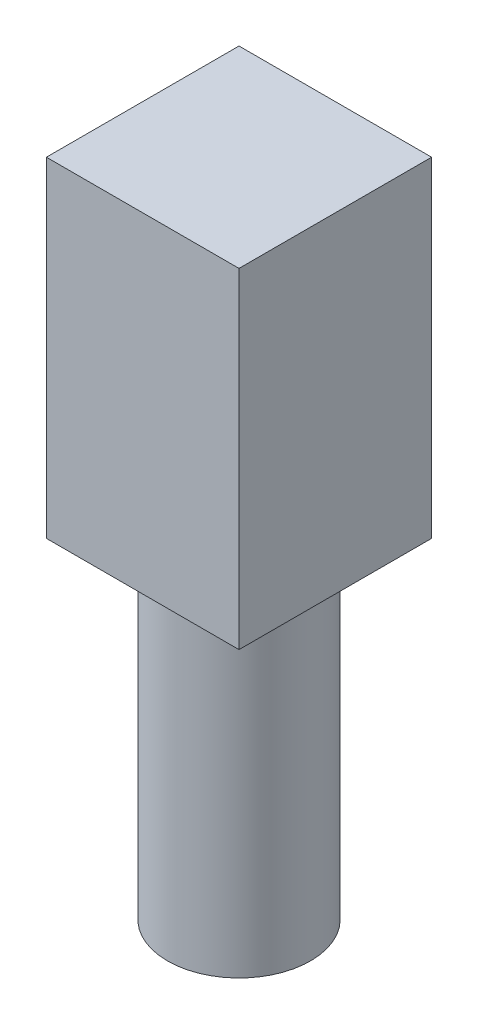
SolidWorks part; units mm, degrees
ref_plane "Front Plane" through (0, 0, 0) normal (0, 0, 1) x (1, 0, 0)
ref_plane "Top Plane" through (0, 0, 0) normal (0, 1, 0) x (1, 0, 0)
ref_plane "Right Plane" through (0, 0, 0) normal (1, 0, 0) x (0, 0, -1)
sketch "Sketch1" plane through (0, 0, 0) normal (0, 1, 0) x (1, 0, 0)
  circle A0 centre (0, 0) radius 1.3
extrude "Boss-Extrude1" add sketch "Sketch1" along normal blind 6
sketch "Sketch2" plane through (0, 6, 0) normal (0, 1, 0) x (1, 0, 0)
  line L1 (1.75, 1.75) -> (-1.75, 1.75)
  line L2 (1.75, 1.75) -> (1.75, -1.75)
  line L3 (1.75, -1.75) -> (-1.75, -1.75)
  line L4 (-1.75, 1.75) -> (-1.75, -1.75)
  line L5 (1.75, 1.75) -> (-1.75, -1.75) construction
  line L6 (1.75, -1.75) -> (-1.75, 1.75) construction
  point P0 (0, 0)
  dimension "D1" = 3.5
  dimension "D2" = 3.5
extrude "Boss-Extrude2" add sketch "Sketch2" along normal blind 6
